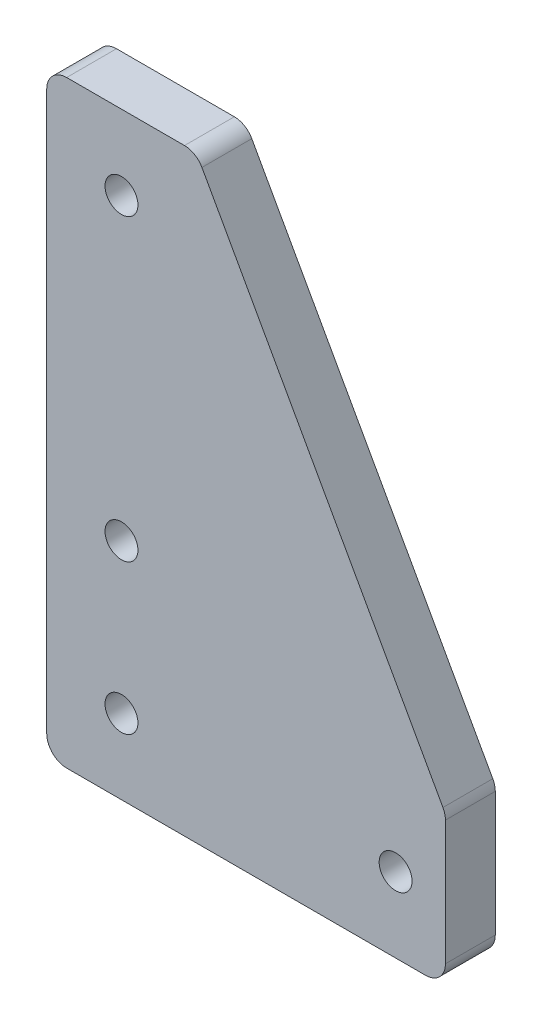
SolidWorks part; units mm, degrees
material "5052-H34"
ref_plane "正面" through (0, 0, 0) normal (0, 0, 1) x (1, 0, 0)
ref_plane "平面" through (0, 0, 0) normal (0, 1, 0) x (1, 0, 0)
ref_plane "右側面" through (0, 0, 0) normal (1, 0, 0) x (0, 0, -1)
sketch "ｽｹｯﾁ1" plane through (0, 0, 0) normal (0, 0, 1) x (1, 0, 0)
  line L0 (0, 0) -> (40, 0)
  line L1 (40, 0) -> (40, 15)
  line L2 (40, 15) -> (15, 60)
  line L3 (15, 60) -> (0, 60)
  line L4 (0, 60) -> (0, 0)
  line L5 (40, 7.5) -> (0, 7.5) construction
  line L6 (7.5, 60) -> (7.5, 0) construction
  circle A0 centre (35, 7.5) radius 1.65
  circle A1 centre (7.5, 7.5) radius 1.65
  circle A2 centre (7.5, 22.5) radius 1.65
  circle A3 centre (7.5, 52.5) radius 1.65
  dimension "D5" = 5
  dimension "D6" = 3.3
  dimension "D7" = 7.5
  dimension "D8" = 30
  dimension "D1" = 15
  dimension "D2" = 15
  dimension "D3" = 40
  dimension "D4" = 60
extrude "ﾎﾞｽ - 押し出し1" add sketch "ｽｹｯﾁ1" along normal blind 5
fillet "ﾌｨﾚｯﾄ1" radius 2 5 edges at (0, 0, 2.5) (40, 0, 2.5) (40, 15, 2.5) (15, 60, 2.5) (0, 60, 2.5)
